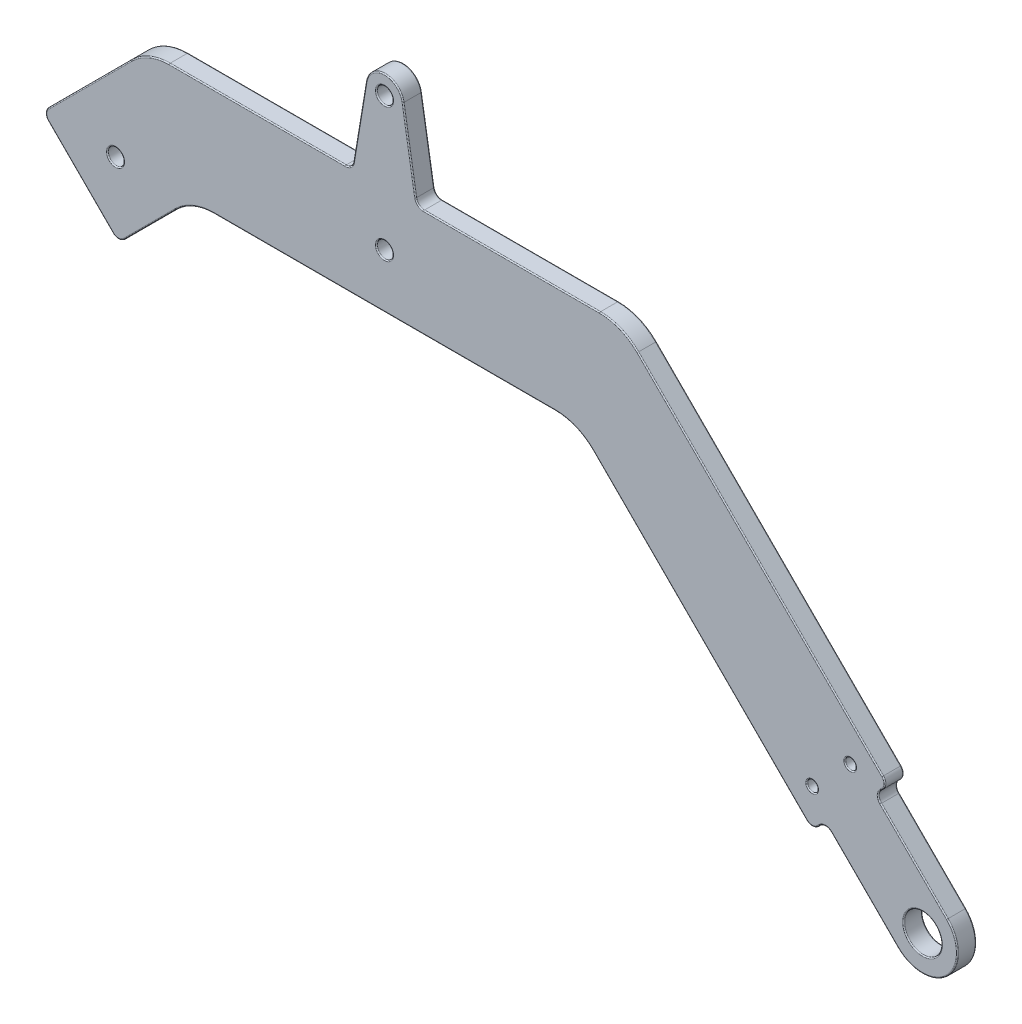
SolidWorks part; units mm, degrees
ref_plane "Front Plane" through (0, 0, 0) normal (0, 0, 1) x (1, 0, 0)
ref_plane "Top Plane" through (0, 0, 0) normal (0, 1, 0) x (1, 0, 0)
ref_plane "Right Plane" through (0, 0, 0) normal (1, 0, 0) x (0, 0, -1)
sketch "Sketch1" plane through (0, 0, 0) normal (0, 0, 1) x (1, 0, 0)
  line L0 (-100, 0) -> (100, 0) construction
  line L1 (-100, 0) -> (0, 100) construction
  line L2 (0, 100) -> (100, 0) construction
  line L3 (0, 0) -> (-50, 50) construction
  line L4 (-40, 60) -> (40, 60) construction
  line L5 (0, 100) -> (0, 60) construction
  circle A0 centre (-100, 0) radius 20
  circle A1 centre (0, 0) radius 20
  circle A2 centre (100, 0) radius 20
  point P3 (0, 0)
  dimension "D5" = 40
  dimension "D1" = 200
  dimension "D2" = 90
  dimension "D3" = 90
  dimension "D4" = 80
sketch "Sketch2" plane through (0, 0, 0) normal (0, 0, 1) x (1, 0, 0)
  line L0 (-56.5165, 43.4835) -> (-40, 60) construction
  line L1 (-100, 0) -> (0, 100) construction
  line L2 (-40, 60) -> (40, 60) construction
  line L3 (40, 60) -> (86.565, 13.435) construction
  line L4 (0, 100) -> (100, 0) construction
  line L5 (-49.4454, 36.4124) -> (-35.8579, 50)
  line L6 (-35.8579, 50) -> (35.8579, 50)
  line L7 (35.8579, 50) -> (79.4939, 6.364)
  line L8 (-63.5876, 50.5546) -> (-44.1421, 70)
  line L9 (-44.1421, 70) -> (44.1421, 70)
  line L10 (44.1421, 70) -> (93.636, 20.5061)
  line L11 (-63.5876, 50.5546) -> (-49.4454, 36.4124)
  line L12 (79.4939, 6.364) -> (93.636, 20.5061)
  line L13 (86.565, 13.435) -> (100, 0) construction
  line L14 (81.9688, 8.8388) -> (95.4038, -4.5962)
  line L15 (91.1612, 18.0312) -> (104.5962, 4.5962)
  line L16 (75.9584, 9.8995) -> (90.1005, 24.0416) construction
  line L17 (0, 100) -> (0, 60) construction
  line L18 (-3.4532, 85.4203) -> (-6, 70)
  line L19 (3.4532, 85.4203) -> (6, 70)
  circle A0 centre (100, 0) radius 3.5
  circle A1 centre (100, 0) radius 10 construction
  arc A2 (95.4038, -4.5962) -> (104.5962, 4.5962) centre (100, 0) ccw
  circle A3 centre (79.4939, 13.435) radius 1
  circle A4 centre (86.565, 20.5061) radius 1
  circle A5 centre (0, 60) radius 1.5
  circle A6 centre (0, 84.85) radius 1.5
  arc A7 (3.4532, 85.4203) -> (-3.4532, 85.4203) centre (0, 84.85) ccw
  circle A8 centre (-50, 50) radius 1.5
  circle A9 centre (0, 84.85) radius 3.5 construction
  point P42 (0, 70)
  point P46 (3.5, 82)
  dimension "D4" = 20
  dimension "D5" = 7
  dimension "D6" = 3
  dimension "D9" = 2
  dimension "D12" = 3
  dimension "D17" = 3
  dimension "D3" = 27.5
  dimension "D7" = 19
  dimension "D8" = 10
  dimension "D10" = 5
  dimension "D11" = 5
  dimension "D13" = 14.85
  dimension "D15" = 6
  dimension "D16" = 6
  dimension "D1" = 10
  dimension "D2" = 10
  dimension "D14" = 2
sketch "Sketch3" plane through (0, 0, 0) normal (0, 0, 1) x (1, 0, 0)
  line L0 (-100, 0) -> (-50, 50) construction
  line L1 (-50, 50) -> (-13.435, 13.435) construction
  line L2 (-79.4939, 6.364) -> (-50, 35.8579)
  line L3 (-50, 35.8579) -> (-20.5061, 6.364)
  line L4 (-93.636, 20.5061) -> (-50, 64.1421)
  line L5 (-50, 64.1421) -> (-6.364, 20.5061)
  line L6 (-93.636, 20.5061) -> (-79.4939, 6.364)
  line L7 (-20.5061, 6.364) -> (-6.364, 20.5061)
  line L8 (-107.0711, 7.0711) -> (-50, 64.1421) construction
  line L9 (-92.9289, -7.0711) -> (-50, 35.8579) construction
  line L10 (-104.534, 4.6576) -> (-90.9809, 17.8509)
  line L11 (-81.9688, 8.8388) -> (-95.4038, -4.5962)
  line L12 (-18.0312, 8.8388) -> (-4.5962, -4.5962)
  line L13 (-8.8388, 18.0312) -> (4.5962, 4.5962)
  line L14 (-90.1005, 24.0416) -> (-75.9584, 9.8995) construction
  line L15 (-24.0416, 9.8995) -> (-9.8995, 24.0416) construction
  circle A0 centre (-100, 0) radius 10 construction
  circle A1 centre (-100, 0) radius 3.5
  circle A2 centre (0, 0) radius 10 construction
  circle A3 centre (0, 0) radius 3.5
  arc A4 (-104.534, 4.6576) -> (-95.4038, -4.5962) centre (-100, 0) ccw
  arc A5 (-4.5962, -4.5962) -> (4.5962, 4.5962) centre (0, 0) ccw
  circle A6 centre (-100, 0) radius 20 construction
  circle A7 centre (-86.565, 20.5061) radius 1
  circle A8 centre (-100, 0) radius 6.5 construction
  circle A9 centre (0, 0) radius 6.5 construction
  circle A10 centre (-79.4939, 13.435) radius 1
  circle A11 centre (-20.5061, 13.435) radius 1
  circle A12 centre (-13.435, 20.5061) radius 1
  point P23 (-86.565, 13.435)
  point P29 (-93.5, 0)
  point P31 (6.5, 0)
  dimension "D1" = 20
  dimension "D2" = 7
  dimension "D8" = 2
  dimension "D10" = 5
  dimension "D6" = 19
  dimension "D7" = 19
  dimension "D9" = 5
  dimension "D11" = 5
  dimension "D12" = 5
  dimension "D3" = 3
  dimension "D4" = 10
  dimension "D5" = 10
sketch "Sketch4" plane through (0, 0, 0) normal (0, 0, 1) x (1, 0, 0)
  line L0 (-57.5, 93.3579) -> (57.5, 93.3579)
  line L1 (57.5, 93.3579) -> (57.5, 83.3579)
  line L2 (57.5, 83.3579) -> (44.1421, 70)
  line L3 (44.1421, 70) -> (-44.1421, 70)
  line L4 (-44.1421, 70) -> (-57.5, 83.3579)
  line L5 (-57.5, 83.3579) -> (-57.5, 93.3579)
  line L6 (-4, 60) -> (-4, 70)
  line L7 (4, 60) -> (4, 70)
  line L8 (-22.5, 84.8579) -> (22.5, 84.8579) construction
  line L9 (-22.5, 89.3579) -> (22.5, 89.3579)
  line L10 (-22.5, 80.3579) -> (22.5, 80.3579)
  line L11 (-63.5876, 50.5546) -> (-44.1421, 70) construction
  circle A0 centre (0, 60) radius 1.5 construction
  circle A1 centre (0, 60) radius 1.5
  arc A2 (-4, 60) -> (4, 60) centre (0, 60) ccw
  arc A3 (-22.5, 89.3579) -> (-22.5, 80.3579) centre (-22.5, 84.8579) ccw
  circle A4 centre (0, 60) radius 4 construction
  arc A5 (22.5, 80.3579) -> (22.5, 89.3579) centre (22.5, 84.8579) ccw
  point P10 (4, 60)
  point P12 (0, 93.3579)
  point P20 (0, 84.8579)
  dimension "D7" = 4.5
  dimension "D1" = 115
  dimension "D2" = 10
  dimension "D4" = 9
  dimension "D5" = 45
  dimension "D6" = 4
  dimension "D3" = 2.5
sketch "Sketch5" plane through (0, 0, 0) normal (0, 0, 1) x (1, 0, 0)
  line L0 (81.9688, 8.8388) -> (95.4038, -4.5962) construction
  line L1 (91.1612, 18.0312) -> (104.5962, 4.5962) construction
  line L2 (-3.4532, 85.4203) -> (-6, 70) construction
  line L3 (3.4532, 85.4203) -> (6, 70) construction
  line L4 (81.9688, 8.8388) -> (95.4038, -4.5962)
  line L5 (91.1612, 18.0312) -> (104.5962, 4.5962)
  line L6 (-3.4532, 85.4203) -> (-6, 70)
  line L7 (3.4532, 85.4203) -> (6, 70)
  line L8 (93.636, 20.5061) -> (44.1421, 70)
  line L9 (79.4939, 6.364) -> (93.636, 20.5061)
  line L10 (35.8579, 50) -> (79.4939, 6.364)
  line L11 (-35.8579, 50) -> (35.8579, 50)
  line L12 (-49.4454, 36.4124) -> (-35.8579, 50)
  line L13 (-63.5876, 50.5546) -> (-49.4454, 36.4124)
  line L14 (-44.1421, 70) -> (-63.5876, 50.5546)
  line L15 (44.1421, 70) -> (-44.1421, 70)
  line L16 (93.636, 20.5061) -> (44.1421, 70)
  line L17 (79.4939, 6.364) -> (81.9688, 8.8388)
  line L18 (35.8579, 50) -> (79.4939, 6.364)
  line L19 (-35.8579, 50) -> (35.8579, 50)
  line L20 (-49.4454, 36.4124) -> (-35.8579, 50)
  line L21 (-63.5876, 50.5546) -> (-49.4454, 36.4124)
  line L22 (-44.1421, 70) -> (-63.5876, 50.5546)
  line L23 (44.1421, 70) -> (6, 70)
  line L24 (-6, 70) -> (-44.1421, 70)
  line L25 (91.1612, 18.0312) -> (93.636, 20.5061)
  arc A0 (95.4038, -4.5962) -> (104.5962, 4.5962) centre (100, 0) ccw construction
  circle A1 centre (86.565, 20.5061) radius 1
  circle A2 centre (86.565, 20.5061) radius 1
  circle A3 centre (79.4939, 13.435) radius 1
  circle A4 centre (79.4939, 13.435) radius 1
  circle A5 centre (100, 0) radius 3.5
  circle A6 centre (100, 0) radius 3.5
  circle A7 centre (0, 84.85) radius 1.5
  circle A8 centre (0, 84.85) radius 1.5
  circle A9 centre (0, 60) radius 1.5
  circle A10 centre (0, 60) radius 1.5
  circle A11 centre (-50, 50) radius 1.5
  circle A12 centre (-50, 50) radius 1.5
  arc A13 (3.4532, 85.4203) -> (-3.4532, 85.4203) centre (0, 84.85) ccw construction
  arc A14 (95.4038, -4.5962) -> (104.5962, 4.5962) centre (100, 0) ccw
  arc A15 (3.4532, 85.4203) -> (-3.4532, 85.4203) centre (0, 84.85) ccw
  dimension "D1" = 0
  dimension "D2" = 0
  dimension "D3" = 0
  dimension "D4" = 0
  dimension "D5" = 0
  dimension "D6" = 0
  dimension "D7" = 0
extrude "Boss-Extrude1" add sketch "Sketch5" along normal blind 3.5
fillet "Fillet1" radius 10 4 edges at (35.8579, 50, 1.75) (-35.8579, 50, 1.75) (44.1421, 70, 1.75) (-44.1421, 70, 1.75)
fillet "Fillet2" radius 1.5 8 edges at (-49.4454, 36.4124, 1.75) (-63.5876, 50.5546, 1.75) (-6, 70, 1.75) (6, 70, 1.75) (93.636, 20.5061, 1.75) (91.1612, 18.0312, 1.75) (81.9688, 8.8388, 1.75) (79.4939, 6.364, 1.75)
fillet "Fillet3" radius 0.2 68 edges at (-48.5, 50, 0) (-48.5, 50, 3.5) (1.5, 60, 0) (1.5, 60, 3.5) (1.5, 84.85, 0) (1.5, 84.85, 3.5) (103.5, 0, 0) (103.5, 0, 3.5) (80.4939, 13.435, 0) (80.4939, 13.435, 3.5) (87.565, 20.5061, 0) (87.565, 20.5061, 3.5) (23.6363, 70, 0) (4.6229, 78.3379, 0) (0, 88.35, 0) (-4.6229, 78.3379, 0) (-23.6363, 70, 0) (-54.799, 59.3431, 0) (-56.5165, 43.4835, 0) (-43.5858, 42.2721, 0) (0, 50, 0) (58.61, 27.2478, 0) (80.7313, 7.6014, 0) (89.2166, 1.591, 0) (104.5962, -4.5962, 0) (98.409, 10.7834, 0) (92.3986, 19.2687, 0) (69.8232, 44.3189, 0) (4.6229, 78.3379, 3.5) (0, 88.35, 3.5) (-4.6229, 78.3379, 3.5) (-23.6363, 70, 3.5) (-54.799, 59.3431, 3.5) (-56.5165, 43.4835, 3.5) (-43.5858, 42.2721, 3.5) (0, 50, 3.5) (58.61, 27.2478, 3.5) (80.7313, 7.6014, 3.5) (89.2166, 1.591, 3.5) (104.5962, -4.5962, 3.5) (98.409, 10.7834, 3.5) (92.3986, 19.2687, 3.5) (69.8232, 44.3189, 3.5) (-43.8268, 69.2388, 0) (43.8268, 69.2388, 0) (-43.8268, 69.2388, 3.5) (43.8268, 69.2388, 3.5) (35.5426, 49.2388, 0) (35.5426, 49.2388, 3.5) (-35.5426, 49.2388, 0) (-35.5426, 49.2388, 3.5) (79.4939, 6.9853, 0) (93.0147, 20.5061, 0) (-62.9663, 50.5546, 0) (-49.4454, 37.0337, 0) (79.4939, 6.9853, 3.5) (93.0147, 20.5061, 3.5) (-62.9663, 50.5546, 3.5) (-49.4454, 37.0337, 3.5) (-6.3022, 70.3562, 0) (-6.3022, 70.3562, 3.5) (6.3022, 70.3562, 0) (6.3022, 70.3562, 3.5) (91.7825, 18.0312, 0) (91.7825, 18.0312, 3.5) (81.9688, 8.2175, 0) (81.9688, 8.2175, 3.5) (23.6363, 70, 3.5)
